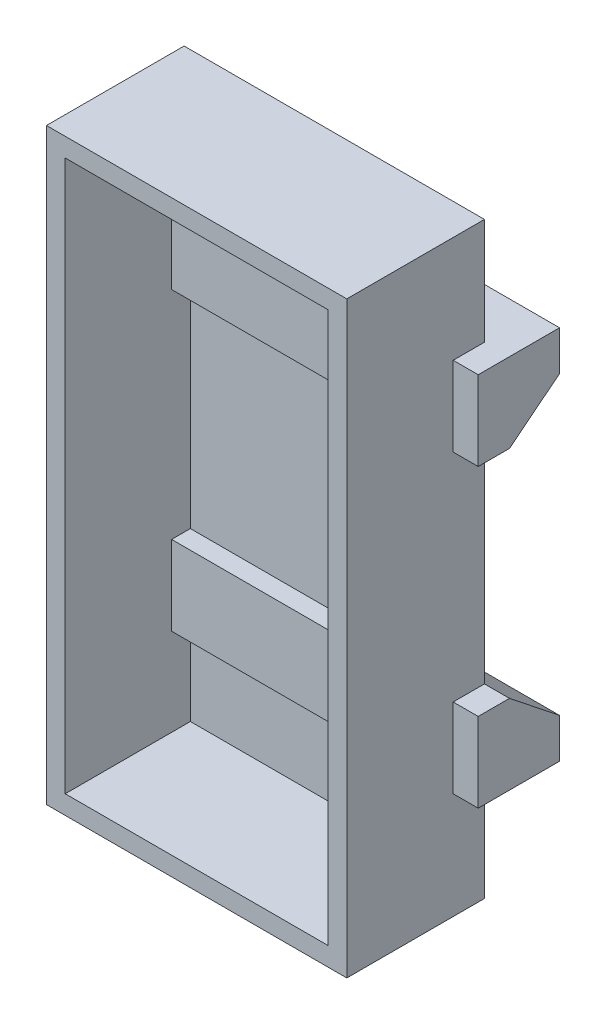
SolidWorks part; units mm, degrees
ref_plane "Front Plane" through (0, 0, 0) normal (0, 0, 1) x (1, 0, 0)
ref_plane "Top Plane" through (0, 0, 0) normal (0, 1, 0) x (1, 0, 0)
ref_plane "Right Plane" through (0, 0, 0) normal (1, 0, 0) x (0, 0, -1)
sketch "草图1" plane through (0, 0, 0) normal (0, 0, 1) x (1, 0, 0)
  line L1 (-24.8629, -20.7117) -> (-0.8629, -20.7117)
  line L2 (-24.8629, -20.7117) -> (-24.8629, -67.7117)
  line L3 (-24.8629, -67.7117) -> (-0.8629, -67.7117)
  line L4 (-0.8629, -20.7117) -> (-0.8629, -67.7117)
extrude "凸台-拉伸1" add sketch "草图1" along normal blind 11
sketch "草图2" plane through (0, 0, 11) normal (0, 0, 1) x (1, 0, 0)
  line L0 (-0.8629, -20.7117) -> (-24.8629, -20.7117) construction
  line L1 (-23.3629, -22.2117) -> (-2.3629, -22.2117)
  line L2 (-23.3629, -22.2117) -> (-23.3629, -66.2117)
  line L3 (-23.3629, -66.2117) -> (-2.3629, -66.2117)
  line L4 (-2.3629, -22.2117) -> (-2.3629, -66.2117)
  line L5 (-0.8629, -67.7117) -> (-0.8629, -20.7117) construction
  line L6 (-24.8629, -67.7117) -> (-0.8629, -67.7117) construction
  line L7 (-24.8629, -20.7117) -> (-24.8629, -67.7117) construction
  dimension "D1" = 1.5
  dimension "D2" = 1.5
  dimension "D3" = 1.5
  dimension "D4" = 1.5
extrude "切除-拉伸1" cut sketch "草图2" against normal blind 10
sketch "草图3" plane through (-24.8629, 0, 0) normal (-1, 0, 0) x (0, 0, 1)
  line L0 (11, -44.2117) -> (-16.9463, -44.2117) construction
  line L3 (-4, -29.2117) -> (2.5, -29.2117)
  line L4 (-4, -29.2117) -> (-4, -35.5645)
  line L5 (-4, -35.5645) -> (2.5, -35.5645)
  line L6 (2.5, -29.2117) -> (2.5, -35.5645)
  line L8 (2.5, -59.2117) -> (2.5, -52.8588)
  line L9 (-4, -52.8588) -> (2.5, -52.8588)
  line L10 (-4, -59.2117) -> (-4, -52.8588)
  line L11 (-4, -59.2117) -> (2.5, -59.2117)
extrude "凸台-拉伸2" add sketch "草图3" against normal blind 26
sketch "草图4" plane through (-24.8629, 0, 0) normal (-1, 0, 0) x (0, 0, 1)
  line L0 (11, -44.2117) -> (36.8864, -44.2117) construction
  line L1 (-4, -29.2117) -> (3, -29.2117)
  line L2 (-4, -29.2117) -> (-4, -35.5645)
  line L3 (-4, -35.5645) -> (3, -35.5645)
  line L4 (3, -29.2117) -> (3, -35.5645)
  line L6 (3, -59.2117) -> (3, -52.8588)
  line L7 (-4, -52.8588) -> (3, -52.8588)
  line L8 (-4, -59.2117) -> (-4, -52.8588)
  line L9 (-4, -59.2117) -> (3, -59.2117)
extrude "凸台-拉伸3" add sketch "草图4" along normal blind 2
sketch "草图6" plane through (-26.8629, 0, 0) normal (-1, 0, 0) x (0, 0, 1)
  line L0 (11, -44.2117) -> (-18.6604, -44.2117) construction
  line L2 (0, -35.5645) -> (-4, -32.3881)
  line L3 (-4, -29.2117) -> (-4, -35.5645) construction
  line L4 (-4, -35.5645) -> (3, -35.5645) construction
  line L5 (-4, -35.5645) -> (0, -35.5645)
  line L6 (-4, -32.3881) -> (-4, -35.5645)
  line L7 (0, -52.8588) -> (-4, -56.0353)
  line L8 (-4, -52.8588) -> (0, -52.8588)
  line L9 (-4, -56.0353) -> (-4, -52.8588)
extrude "切除-拉伸2" cut sketch "草图6" against normal blind 35
